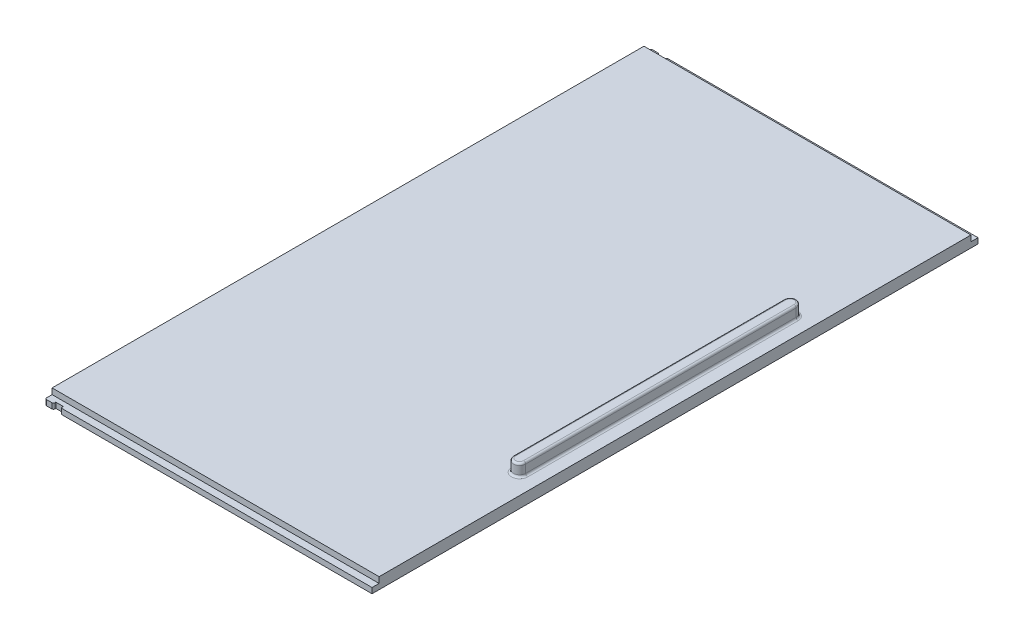
SolidWorks part; units mm, degrees
ref_plane "Front Plane" through (0, 0, 0) normal (0, 0, 1) x (1, 0, 0)
ref_plane "Top Plane" through (0, 0, 0) normal (0, 1, 0) x (1, 0, 0)
ref_plane "Right Plane" through (0, 0, 0) normal (1, 0, 0) x (0, 0, -1)
sketch "Sketch1" plane through (0, 0, 0) normal (0, 1, 0) x (1, 0, 0)
  line L1 (0, 0) -> (81, 0)
  line L2 (0, 0) -> (0, 153)
  line L3 (0, 153) -> (81, 153)
  line L4 (81, 0) -> (81, 153)
  dimension "D1" = 153
  dimension "D2" = 81
extrude "Boss-Extrude1" add sketch "Sketch1" along normal blind 3
sketch "Sketch2" plane through (81, 0, 0) normal (1, 0, 0) x (0, 0, -1)
  line L0 (0, 0) -> (153, 0) construction
  line L1 (0, 3) -> (3, 3)
  line L2 (0, 3) -> (0, 0)
  line L3 (0, 0) -> (1.25, 0)
  line L4 (3, 3) -> (3, 1.75)
  line L5 (3, 1.75) -> (1.25, 1.75)
  line L6 (1.25, 1.75) -> (1.25, 0)
  line L7 (151.75, 0) -> (153, 0)
  line L11 (76.5, 3) -> (76.5, 0) construction
  line L12 (0, 3) -> (153, 3) construction
  line L22 (153, 3) -> (150, 3)
  line L25 (151.75, 1.75) -> (150, 1.75)
  line L26 (150, 1.75) -> (150, 3)
  line L31 (151.75, 1.75) -> (151.75, 0)
  line L35 (153, 3) -> (153, 0)
  dimension "D1" = 3
  dimension "D2" = 1.25
  dimension "D3" = 1.25
  dimension "D4" = 3
extrude "Cut-Extrude2" cut sketch "Sketch2" against normal up to surface (81 mm away) up to face at (0, 1.5, -76.5)
sketch "Sketch4" plane through (81, 0, 0) normal (1, 0, 0) x (0, 0, -1)
  line L17 (76.5, 3) -> (76.5, 0) construction
  line L18 (3, 3) -> (150, 3) construction
  line L19 (1.25, 0) -> (151.75, 0) construction
  line L36 (3.2, 3) -> (3, 3)
  line L37 (3, 3) -> (3, 1.75)
  line L38 (3, 1.75) -> (3, 3) construction
  line L39 (1.45, 0) -> (1.45, 1.55)
  line L40 (1.45, 1.55) -> (3.2, 1.55)
  line L41 (3.2, 1.55) -> (3.2, 3)
  line L42 (1.45, 0) -> (1.45, 1.55)
  line L43 (1.45, 1.55) -> (3.2, 1.55)
  line L44 (3.2, 1.55) -> (3.2, 3)
  line L45 (3, 1.75) -> (1.25, 1.75)
  line L46 (1.25, 1.75) -> (1.25, 0)
  line L47 (1.25, 0) -> (1.45, 0)
  line L48 (151.75, 0) -> (151.55, 0)
  line L49 (151.75, 1.75) -> (151.75, 0)
  line L50 (150, 1.75) -> (151.75, 1.75)
  line L51 (149.8, 1.55) -> (149.8, 3)
  line L52 (151.55, 1.55) -> (149.8, 1.55)
  line L53 (151.55, 0) -> (151.55, 1.55)
  line L54 (150, 3) -> (150, 1.75)
  line L55 (149.8, 3) -> (150, 3)
  dimension "D1" = 0.2
extrude "Cut-Extrude3" cut sketch "Sketch4" against normal up to surface (81 mm away) up to face at (0, 1.625, -76.5)
sketch "Sketch6" plane through (0, 0, -1.45) normal (0, 0, 1) x (1, 0, 0)
  line L0 (3, 0.775) -> (0, 0.775) construction
  line L1 (0, 1.55) -> (0, 0) construction
  line L3 (2.075, 0) -> (3.925, 0)
  line L4 (2.075, 0) -> (2.075, 1.55)
  line L5 (2.075, 1.55) -> (3.925, 1.55)
  line L6 (3.925, 0) -> (3.925, 1.55)
  line L7 (2.075, 0) -> (3.925, 1.55) construction
  line L8 (2.075, 1.55) -> (3.925, 0) construction
  line L9 (0, 1.55) -> (81, 1.55) construction
  line L10 (0, 1.55) -> (81, 1.55) construction
  dimension "D1" = 3
  dimension "D3" = 1.85
  dimension "D4" = 0.775
extrude "Cut-Extrude5" cut sketch "Sketch6" against normal blind 0.6
fillet "Fillet6" radius 0.4 1 edges at (2.075, 0.775, -1.45)
chamfer "Chamfer2" distance 0.2 angle 45 1 edges at (3.925, 0.775, -1.45)
sketch "Sketch7" plane through (0, 0, -151.55) normal (0, 0, -1) x (-1, 0, 0)
  line L0 (-3, 0.775) -> (0, 0.775) construction
  line L3 (-2.075, 1.55) -> (-3.925, 1.55)
  line L4 (-2.075, 1.55) -> (-2.075, 0)
  line L5 (-2.075, 0) -> (-3.925, 0)
  line L6 (-3.925, 1.55) -> (-3.925, 0)
  line L7 (-2.075, 1.55) -> (-3.925, 0) construction
  line L8 (-2.075, 0) -> (-3.925, 1.55) construction
  line L9 (0, 0) -> (0, 1.55) construction
  line L10 (0, 1.55) -> (-81, 1.55) construction
  dimension "D1" = 3
  dimension "D3" = 1.85
  dimension "D4" = 0.775
extrude "Cut-Extrude6" cut sketch "Sketch7" against normal blind 0.6
fillet "Fillet7" radius 0.4 1 edges at (2.075, 0.775, -151.55)
chamfer "Chamfer3" distance 0.2 angle 45 1 edges at (3.925, 0.775, -151.55)
sketch "Sketch9" plane through (0, 3, 0) normal (0, 1, 0) x (1, 0, 0)
  line L0 (76, 43) -> (76, 110) construction
  line L1 (74.5, 43) -> (74.5, 110)
  line L2 (77.5, 43) -> (77.5, 110)
  line L3 (76, 110) -> (76, 149.8) construction
  line L5 (0, 149.8) -> (81, 149.8) construction
  line L14 (76, 43) -> (76, 3.2) construction
  line L15 (0, 3.2) -> (81, 3.2) construction
  line L16 (81, 3.2) -> (81, 149.8) construction
  arc A0 (74.5, 43) -> (77.5, 43) centre (76, 43) ccw
  arc A1 (77.5, 110) -> (74.5, 110) centre (76, 110) ccw
  point P2 (76, 76.5)
  dimension "D1" = 3
  dimension "D2" = 67
  dimension "D3" = 5
sketch "Sketch10" plane through (0, 0, 0) normal (0, -1, 0) x (-1, 0, 0)
  line L1 (0, 1.45) -> (-81, 1.45)
  line L2 (0, 1.45) -> (0, 151.55)
  line L3 (0, 151.55) -> (-81, 151.55)
  line L4 (-81, 1.45) -> (-81, 151.55)
extrude "Cut-Extrude7" cut sketch "Sketch10" against normal blind 0.2
fillet "Fillet8" radius 0.4 2 edges at (0, 0.875, -151.55) (0, 0.875, -1.45)
extrude "Boss-Extrude2" add sketch "Sketch9" along normal blind 3
fillet "Fillet10" radius 0.5 8 edges at (74.5, 3, -76.5) (76, 3, -111.5) (77.5, 3, -76.5) (74.5, 6, -76.5) (76, 6, -111.5) (77.5, 6, -76.5) (76, 6, -41.5) (76, 3, -41.5)
